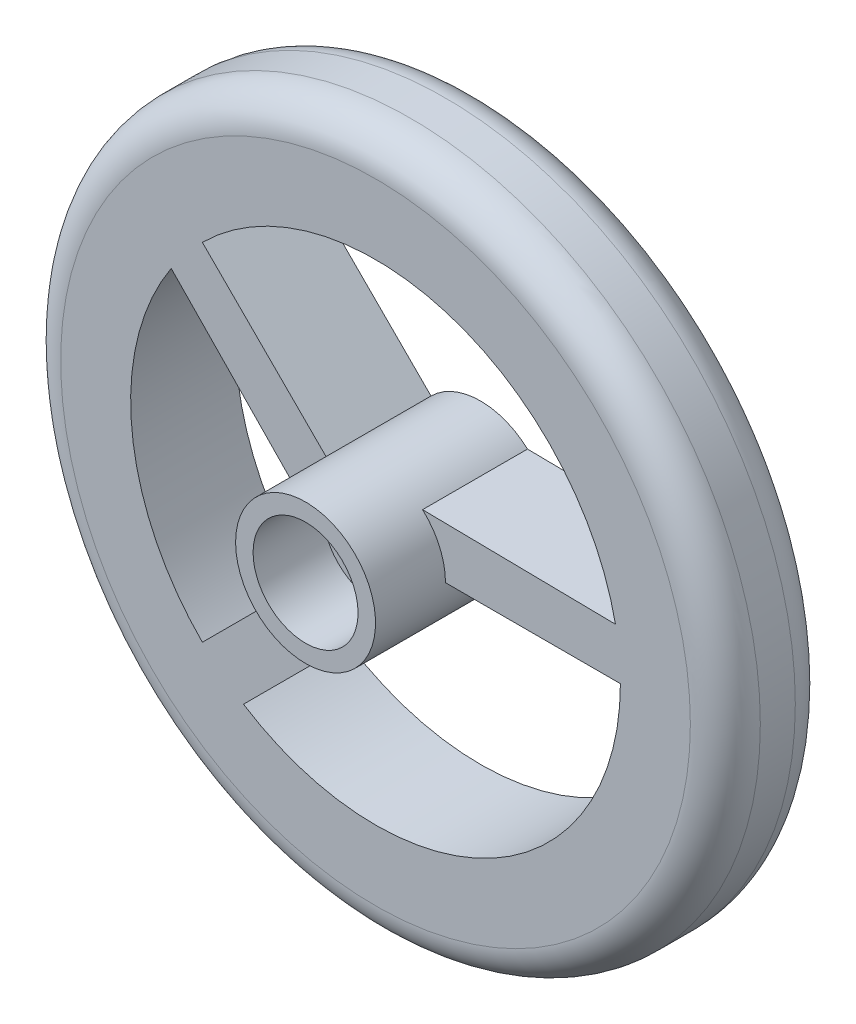
SolidWorks part; units mm, degrees
ref_plane "Front Plane" through (0, 0, 0) normal (0, 0, 1) x (1, 0, 0)
ref_plane "Top Plane" through (0, 0, 0) normal (0, 1, 0) x (1, 0, 0)
ref_plane "Right Plane" through (0, 0, 0) normal (1, 0, 0) x (0, 0, -1)
sketch "Sketch1" plane through (0, 0, 0) normal (0, 0, 1) x (1, 0, 0)
  line L1 (-10.6066, -10.6066) -> (-49.4975, -49.4975)
  line L4 (10.6066, -10.6066) -> (-37.7411, -58.9543)
  line L5 (-10.6066, -10.6066) -> (-49.4967, -49.4967)
  line L6 (-49.2269, -49.7666) -> (-49.4967, -49.4967)
  line L8 (-10.6066, 10.6066) -> (-49.4975, 49.4975)
  line L9 (-10.6066, -10.6066) -> (-58.3969, 38.5979)
  line L12 (15, 0) -> (70, 0)
  line L13 (0, 15) -> (68.5857, 14)
  arc A0 (-58.3969, 38.5979) -> (-49.2269, -49.7666) centre (0, 0) ccw
  circle A1 centre (0, 0) radius 100
  circle A2 centre (0, 0) radius 15
  arc A3 (-37.7411, -58.9543) -> (70, 0) centre (0, 0) ccw
  arc A4 (68.5857, 14) -> (-49.4975, 49.4975) centre (0, 0) ccw
  point P4 (-10.6066, -10.6066)
  point P8 (10.6066, -10.6066)
  point P9 (0, 15)
  dimension "D1" = 200
  dimension "D2" = 140
  dimension "D4" = 15
  dimension "D5" = 15
  dimension "D6" = 15
extrude "Boss-Extrude1" add sketch "Sketch1" along normal blind 30 contours A1 A4 L13 A2 L12 A3 L4 L1 L6 A0 L9 L8 | A2 L9 L13
fillet "Fillet2" radius 10 2 edges at (100, 0, 30) (100, 0, 0)
sketch "Sketch2" plane through (0, 0, 0) normal (0, 0, -1) x (-1, 0, 0)
  circle A0 centre (0, 0) radius 20
  circle A1 centre (0, 0) radius 15
  dimension "D1" = 40
  dimension "D2" = 30
extrude "Boss-Extrude2" add sketch "Sketch2" against normal blind 50
